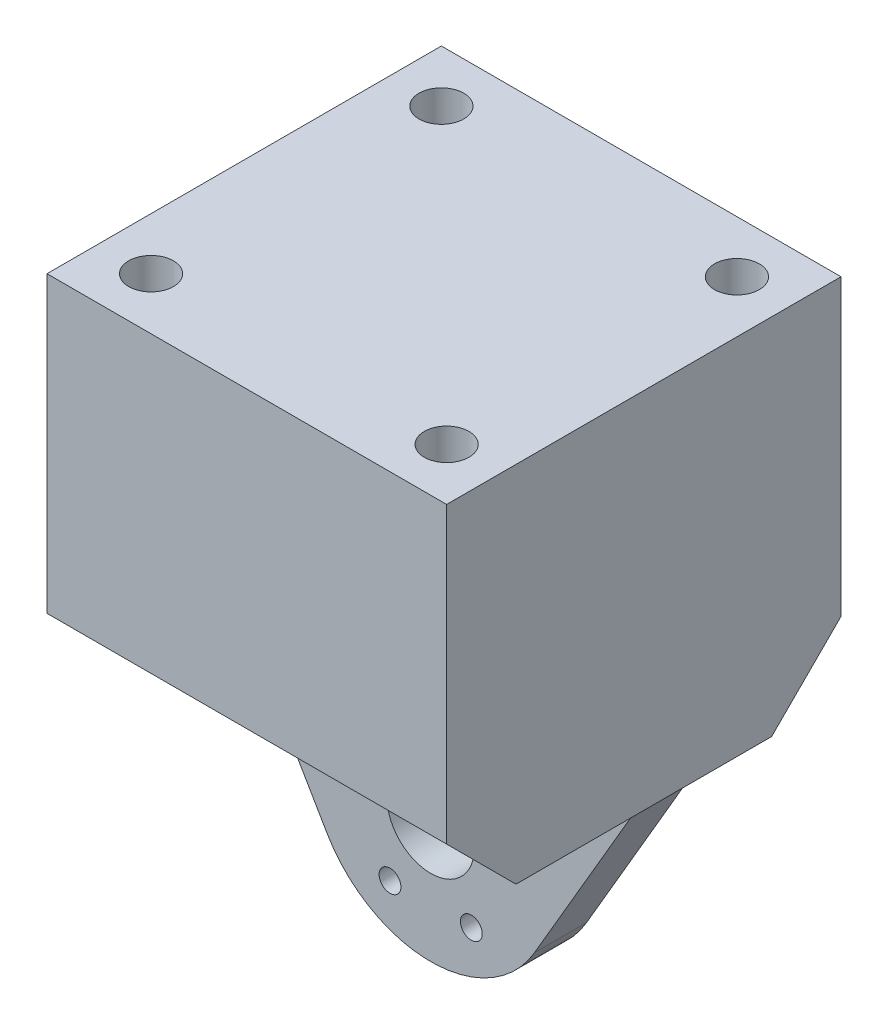
SolidWorks part; units mm, degrees
material "ABS"
ref_plane "Front Plane" through (0, 0, 0) normal (0, 0, 1) x (1, 0, 0)
ref_plane "Top Plane" through (0, 0, 0) normal (0, 1, 0) x (1, 0, 0)
ref_plane "Right Plane" through (0, 0, 0) normal (1, 0, 0) x (0, 0, -1)
sketch "Sketch1" plane through (0, 0, 0) normal (0, 0, 1) x (1, 0, 0)
  line L1 (-18.288, -16.637) -> (18.288, -16.637)
  line L2 (-18.288, -16.637) -> (-18.288, 16.637)
  line L3 (-18.288, 16.637) -> (18.288, 16.637)
  line L4 (18.288, -16.637) -> (18.288, 16.637)
  line L5 (-18.288, -16.637) -> (18.288, 16.637) construction
  line L6 (-18.288, 16.637) -> (18.288, -16.637) construction
  point P0 (0, 0)
  dimension "D1" = 33.274
  dimension "D2" = 36.576
extrude "Bearing Mount Block" add sketch "Sketch1" along normal blind 31.0134 and the other way blind 5.08 contours L3 L4 L1 L2
sketch "Bearing Mount Footprint" plane through (0, -16.637, 0) normal (0, -1, 0) x (1, 0, 0)
  line L0 (-18.288, -5.08) -> (-18.288, 31.0134) construction
  line L1 (-18.288, 20.8534) -> (18.288, 20.8534) construction
  line L2 (-18.288, 20.8534) -> (-18.288, 15.7734) construction
  line L3 (-18.288, 15.7734) -> (18.288, 15.7734) construction
  line L4 (18.288, 20.8534) -> (18.288, 15.7734) construction
  line L5 (18.288, -5.08) -> (18.288, 31.0134) construction
  line L6 (-18.288, 31.0134) -> (18.288, 31.0134) construction
  dimension "D1" = 5.08
  dimension "D2" = 10.16
sketch "Bearing Mount Hole Pattern" plane through (0, -16.637, 0) normal (0, -1, 0) x (1, 0, 0)
  line L1 (-18.288, 18.3134) -> (18.288, 18.3134) construction
  line L2 (-18.288, 20.8534) -> (-18.288, 15.7734) construction
  line L3 (18.288, 20.8534) -> (18.288, 15.7734) construction
  line L4 (-14.2875, 18.3134) -> (14.2875, 18.3134) construction
  point P0 (-14.2875, 18.3134)
  point P1 (14.2875, 18.3134)
  point P15 (0, 18.3134)
  dimension "D1" = 28.575
hole_wizard "CBORE for #4 Socket Head Cap Screw1" positions "3DSketch2" profile "Sketch10" counterbore size "#4" standard "ANSI Inch"
sketch3d "3DSketch2"
  point P0 (-14.2875, -16.637, 18.3134)
  point P3 (14.2875, -16.637, 18.3134)
sketch "Sketch10" plane through (-14.2875, -16.637, 18.3134) normal (1, 0, 0) x (0, 0, -1)
  line L0 (0, 0) -> (0, 16.8556)
  line L1 (0, 16.8556) -> (1.6319, 15.875)
  line L2 (1.6319, 15.875) -> (1.6319, 4.7625)
  line L3 (1.6319, 4.7625) -> (2.0479, 4.7625)
  line L4 (2.0479, 4.7625) -> (2.0479, 0)
  line L5 (2.0479, 0) -> (0, 0)
  line L10 (0, 16.8556) -> (-1.632, 15.875) construction
  line L11 (0, -6.35) -> (0, 107.95) construction
  dimension "Hole Dia." = 3.2639
  dimension "Hole Depth" = 15.875
  dimension "C'Bore Dia." = 4.0957
  dimension "C'Bore Depth" = 4.7625
  dimension "Drill Angle" = 118
sketch "Plate Mounting Hole Pattern" plane through (0, 16.637, 0) normal (0, 1, 0) x (1, 0, 0)
  line L24 (-13.5255, 0.3175) -> (-13.5255, -26.2509)
  line L25 (-13.5255, -26.2509) -> (13.5255, -26.2509)
  line L26 (13.5255, -26.2509) -> (13.5255, 0.3175)
  line L27 (13.5255, 0.3175) -> (-13.5255, 0.3175)
  line L28 (-13.5255, 0.3175) -> (-13.5255, -26.2509) construction
  line L29 (-13.5255, -26.2509) -> (13.5255, -26.2509) construction
  line L30 (13.5255, -26.2509) -> (13.5255, 0.3175) construction
  line L31 (13.5255, 0.3175) -> (-13.5255, 0.3175) construction
  dimension "D1" = 4.7625
hole_wizard "CBORE for #4 Socket Head Cap Screw2" positions "Sketch13" profile "Sketch12" counterbore size "#4" standard "ANSI Inch"
sketch "Sketch13" plane through (0, 16.637, 0) normal (0, 1, 0) x (1, 0, 0)
  point P13 (13.5255, 0.3175)
  point P16 (13.5255, -26.2509)
  point P19 (-13.5255, -26.2509)
  point P22 (-13.5255, 0.3175)
sketch "Sketch12" plane through (13.5255, 16.637, -0.3175) normal (1, 0, 0) x (0, 0, 1)
  line L0 (0, 0) -> (0, 16.8556)
  line L1 (0, 16.8556) -> (1.6319, 15.875)
  line L2 (1.6319, 15.875) -> (1.6319, 4.7625)
  line L3 (1.6319, 4.7625) -> (2.0479, 4.7625)
  line L4 (2.0479, 4.7625) -> (2.0479, 0)
  line L5 (2.0479, 0) -> (0, 0)
  line L10 (0, 16.8556) -> (-1.632, 15.875) construction
  line L11 (0, -6.35) -> (0, 107.95) construction
  dimension "Hole Dia." = 3.2639
  dimension "Hole Depth" = 15.875
  dimension "C'Bore Dia." = 4.0957
  dimension "C'Bore Depth" = 4.7625
  dimension "Drill Angle" = 118
ref_plane "Encoder Mounting Plane" through (0, 0, 14.1859) normal (0, 0, 1) x (1, 0, 0)
sketch "Sketch14" plane through (0, 0, 14.1859) normal (0, 0, 1) x (1, 0, 0)
  line L0 (18.288, -16.637) -> (9.5003, -31.7032)
  line L1 (-18.288, -16.637) -> (-9.5003, -31.7032)
  line L2 (18.288, -16.637) -> (-18.288, -16.637)
  arc A0 (9.5003, -31.7032) -> (-9.5003, -31.7032) centre (0, -26.162) cw
  circle A1 centre (0, -26.162) radius 4.0005
  dimension "D2" = 10.9982
  dimension "D3" = 8.001
  dimension "D1" = 9.525
extrude "Encoder Mounting Flange" add sketch "Sketch14" against normal blind 4.7625
hole_wizard "Encoder Mounting Holes (#3-48)" positions "Sketch17" profile "Sketch16" tap size "#3-48" standard "ANSI Inch"
sketch "Sketch17" plane through (0, 0, 9.4234) normal (0, 0, -1) x (-1, 0, 0)
  line L0 (3.7211, -19.7169) -> (-3.7211, -32.6071) construction
  line L2 (-3.7211, -19.7169) -> (3.7211, -32.6071) construction
  line L4 (7.4422, -26.162) -> (-7.4422, -26.162) construction
  circle A0 centre (0, -26.162) radius 7.4422 construction
  point P6 (-3.7211, -32.6071)
  point P8 (3.7211, -19.7169)
  point P10 (3.7211, -32.6071)
  point P12 (-3.7211, -19.7169)
  dimension "D1" = 14.8844
  dimension "D2" = 60
  dimension "D3" = 60
sketch "Sketch16" plane through (3.7211, -32.6071, 9.4234) normal (1, 0, 0) x (0, 1, 0)
  line L0 (0, 0) -> (0, 8.219)
  line L1 (0, 8.219) -> (0.9969, 7.62)
  line L2 (0.9969, 7.62) -> (0.9969, 0)
  line L5 (0.9969, 0) -> (0, 0)
  line L10 (0, 8.219) -> (-0.997, 7.62) construction
  line L11 (0, -6.35) -> (0, 107.95) construction
  dimension "Tap Drill Dia." = 1.9939
  dimension "Tap Drill Depth" = 7.62
  dimension "Drill Angle" = 118
chamfer "Material Reduction Chamfer" distance 6.35 angle 45 1 edges at (0, -16.637, 31.0134)
chamfer "Material Reduction Chamfer 2" distance 6.35 angle 45 1 edges at (0, -16.637, -5.08)
sketch "Sketch18" plane through (0, 0, 9.4234) normal (0, 0, -1) x (-1, 0, 0)
  line L0 (-18.288, -24.7904) -> (18.288, -24.7904) construction
  line L1 (12.6257, -24.7904) -> (-12.6257, -24.7904)
  arc A0 (12.6257, -24.7904) -> (-12.6257, -24.7904) centre (0, -26.162) ccw
  dimension "D1" = 12.7
extrude "Encoder Clearance Cut" cut sketch "Sketch18" along normal through all
chamfer "Tapping Chamfer" distance 0.762 angle 45 4 edges at (-4.7181, -32.6071, 9.4234) (-4.718, -19.7169, 9.4234) (2.7242, -19.7169, 9.4234) (2.7241, -32.6071, 9.4234)
